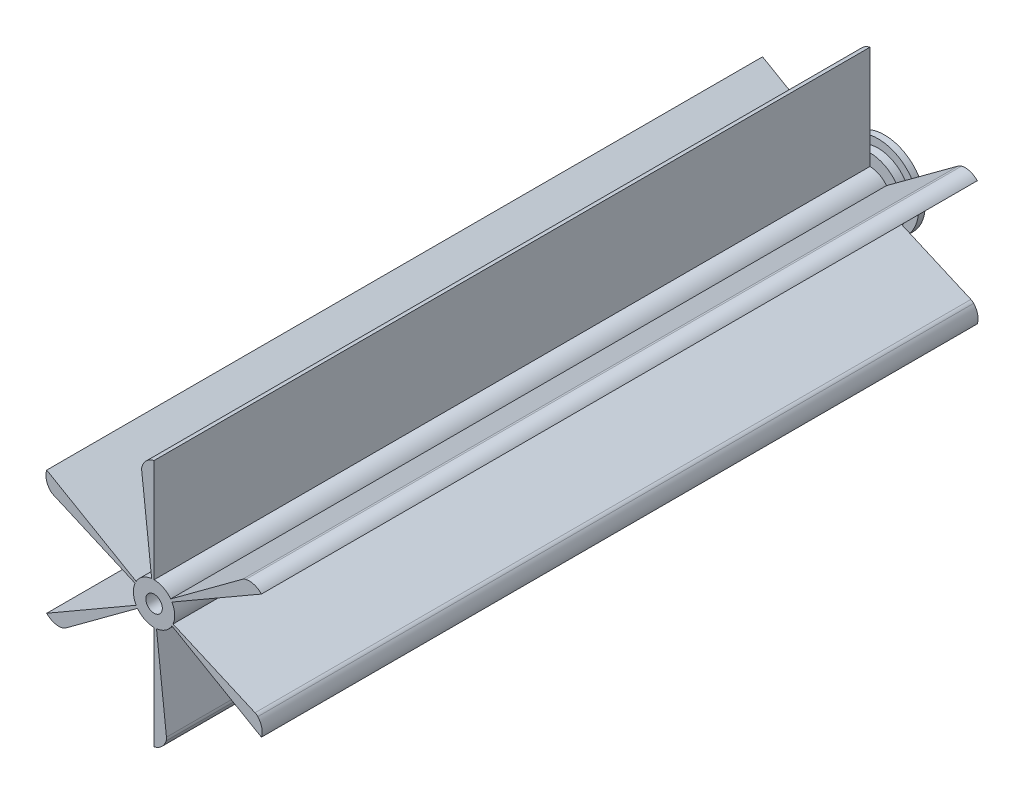
SolidWorks part; units mm, degrees
ref_plane "Front Plane" through (0, 0, 0) normal (0, 0, 1) x (1, 0, 0)
ref_plane "Top Plane" through (0, 0, 0) normal (0, 1, 0) x (1, 0, 0)
ref_plane "Right Plane" through (0, 0, 0) normal (1, 0, 0) x (0, 0, -1)
sketch "Sketch1" plane through (0, 0, 0) normal (0, 0, 1) x (1, 0, 0)
  line L0 (0, 6.35) -> (0, 43.6797) construction
  line L1 (0, 0) -> (46.9897, 0) construction
  line L2 (-0.744, 6.3063) -> (-3.809, 33.6315)
  line L3 (0, 6.35) -> (0, 38.1)
  line L4 (5.0894, 3.7975) -> (27.2213, 20.1145)
  line L5 (5.4993, 3.175) -> (32.9956, 19.05)
  line L6 (5.8334, -2.5088) -> (31.0303, -13.5171)
  line L7 (5.4993, -3.175) -> (32.9956, -19.05)
  line L8 (0.744, -6.3063) -> (3.809, -33.6315)
  line L9 (0, -6.35) -> (0, -38.1)
  line L10 (-5.0894, -3.7975) -> (-27.2213, -20.1145)
  line L11 (-5.4993, -3.175) -> (-32.9956, -19.05)
  line L12 (-5.8334, 2.5088) -> (-31.0303, 13.5171)
  line L13 (-5.4993, 3.175) -> (-32.9956, 19.05)
  circle A0 centre (0, 0) radius 6.35
  circle A1 centre (0, 0) radius 38.1 construction
  arc A2 (-3.7067, 34.6805) -> (0, 38.1) centre (1.1369, 33.1489) cw
  arc A3 (-0.744, 6.3063) -> (0, 6.35) centre (0, 0) cw
  arc A4 (28.1809, 20.5503) -> (32.9956, 19.05) centre (29.2762, 15.5898) cw
  arc A5 (5.0894, 3.7975) -> (5.4993, 3.175) centre (0, 0) cw
  arc A6 (31.8875, -14.1302) -> (32.9956, -19.05) centre (28.1393, -17.559) cw
  arc A7 (5.8334, -2.5088) -> (5.4993, -3.175) centre (0, 0) cw
  arc A8 (3.7067, -34.6805) -> (0, -38.1) centre (-1.1369, -33.1489) cw
  arc A9 (0.744, -6.3063) -> (0, -6.35) centre (0, 0) cw
  arc A10 (-28.1809, -20.5503) -> (-32.9956, -19.05) centre (-29.2762, -15.5898) cw
  arc A11 (-5.0894, -3.7975) -> (-5.4993, -3.175) centre (0, 0) cw
  arc A12 (-31.8875, 14.1302) -> (-32.9956, 19.05) centre (-28.1393, 17.559) cw
  arc A13 (-5.8334, 2.5088) -> (-5.4993, 3.175) centre (0, 0) cw
  arc A14 (-3.809, 33.6315) -> (-3.7067, 34.6805) centre (-1.2849, 33.9147) cw
  arc A15 (-31.0303, 13.5171) -> (-31.8875, 14.1302) centre (-30.0134, 15.8446) cw
  arc A16 (27.2213, 20.1145) -> (28.1809, 20.5503) centre (28.7285, 18.0701) cw
  arc A17 (31.0303, -13.5171) -> (31.8875, -14.1302) centre (30.0134, -15.8446) cw
  arc A18 (3.809, -33.6315) -> (3.7067, -34.6805) centre (1.2849, -33.9147) cw
  arc A19 (-27.2213, -20.1145) -> (-28.1809, -20.5503) centre (-28.7285, -18.0701) cw
  point P40 (0, 0)
  point P41 (-3.8585, 34.0721)
  dimension "D1" = 12.7
  dimension "D2" = 76.2
  dimension "D3" = 5.08
  dimension "D6" = 4.8613
  dimension "D8" = 2.54
  dimension "D9" = 2.54
  dimension "D4" = 27.94
  dimension "D5" = 6.4
  dimension "D7" = 6
extrude "Boss-Extrude5" add sketch "Sketch1" along normal blind 220 contours A0 | A18 L8 A0 L9 A8 | A19 L10 A0 L11 A10 | A15 L12 A0 L13 A12 | A14 L2 A0 L3 A2 | A16 L4 A0 L5 A4 | A17 L6 A0 L7 A6
sketch "Sketch9" plane through (0, 0, 0) normal (0, 0, -1) x (-1, 0, 0)
  circle A0 centre (0, 0) radius 10
  dimension "D1" = 20
extrude "Boss-Extrude6" add sketch "Sketch9" along normal blind 2.5
sketch "Sketch8" plane through (0, 0, 0) normal (0, 0, -1) x (-1, 0, 0)
  circle A0 centre (0, 0) radius 6.35
  circle A1 centre (0, 0) radius 2.5
  dimension "D1" = 12.7
  dimension "D2" = 5
sketch "Sketch10" plane through (0, 0, -2.5) normal (0, 0, -1) x (-1, 0, 0)
  circle A0 centre (0, 0) radius 12.5
  dimension "D1" = 25
extrude "Boss-Extrude7" add sketch "Sketch10" along normal blind 2
sketch "Sketch7" plane through (0, 0, 220) normal (0, 0, 1) x (1, 0, 0)
  circle A0 centre (0, 0) radius 2.54
  dimension "D1" = 5.08
extrude "Cut-Extrude1" cut sketch "Sketch7" against normal blind 19 contours A0
sketch "Sketch11" plane through (0, 0, -4.5) normal (0, 0, -1) x (-1, 0, 0)
  line L0 (-1.12, 1.0424) -> (1.12, 1.0424)
  arc A0 (-1.12, 1.0424) -> (1.12, 1.0424) centre (0, 0) ccw
  dimension "D1" = 3.06
  dimension "D2" = 2.24
extrude "Cut-Extrude2" cut sketch "Sketch11" against normal blind 19
